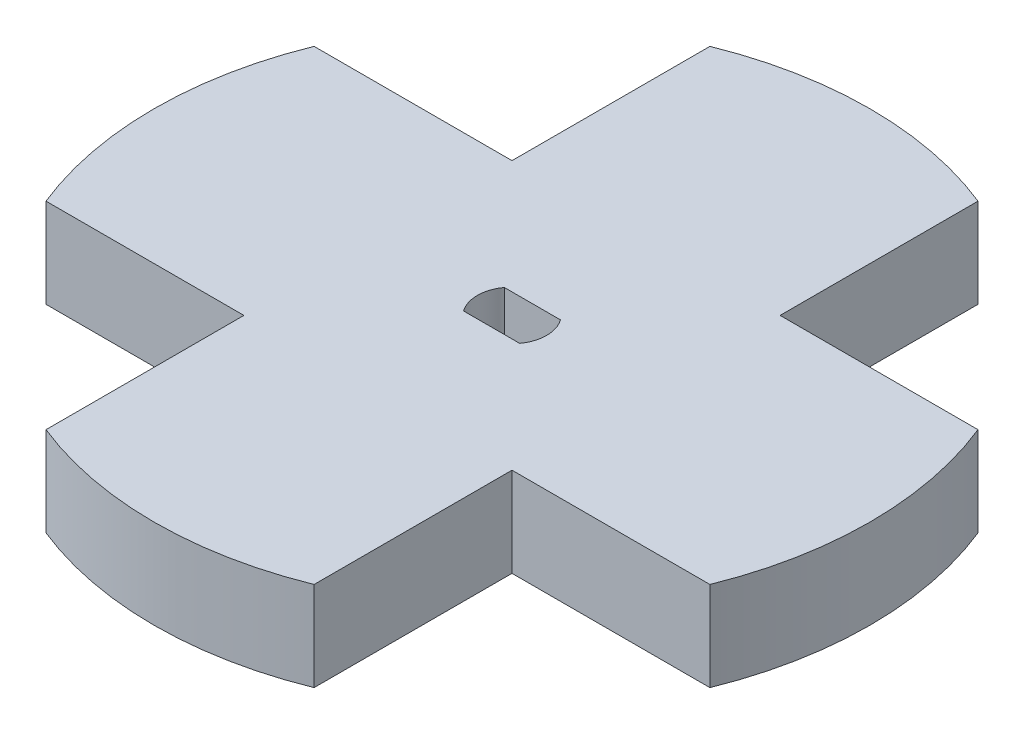
SolidWorks part; units mm, degrees
ref_plane "Front Plane" through (0, 0, 0) normal (0, 0, 1) x (1, 0, 0)
ref_plane "Top Plane" through (0, 0, 0) normal (0, 1, 0) x (1, 0, 0)
ref_plane "Right Plane" through (0, 0, 0) normal (1, 0, 0) x (0, 0, -1)
sketch "Sketch1" plane through (0, 0, 0) normal (0, 1, 0) x (1, 0, 0)
  line L0 (2.129, 43.8841) -> (2.129, 57.9466)
  line L1 (21.179, 43.8841) -> (21.179, 57.9466)
  line L2 (2.129, 24.8341) -> (2.129, 10.7716)
  line L3 (21.179, 24.8341) -> (21.179, 10.7716)
  line L4 (2.129, 43.8841) -> (-11.9336, 43.8841)
  line L5 (21.179, 43.8841) -> (35.2415, 43.8841)
  line L6 (2.129, 24.8341) -> (-11.9336, 24.8341)
  line L7 (21.179, 24.8341) -> (35.2415, 24.8341)
  line L8 (11.654, 35.8069) -> (13.6475, 35.8069)
  line L9 (11.654, 35.8069) -> (9.6604, 35.8069)
  line L10 (11.654, 32.9113) -> (9.6604, 32.9113)
  line L11 (11.654, 32.9113) -> (13.6475, 32.9113)
  arc A0 (35.2415, 24.8341) -> (35.2415, 43.8841) centre (11.654, 34.3591) ccw
  arc A2 (9.6604, 35.8069) -> (9.6604, 32.9113) centre (11.654, 34.3591) ccw
  arc A4 (13.6475, 32.9113) -> (13.6475, 35.8069) centre (11.654, 34.3591) ccw
  arc A5 (21.179, 57.9466) -> (2.129, 57.9466) centre (11.654, 34.3591) ccw
  arc A6 (-11.9336, 43.8841) -> (-11.9336, 24.8341) centre (11.654, 34.3591) ccw
  arc A7 (2.129, 10.7716) -> (21.179, 10.7716) centre (11.654, 34.3591) ccw
extrude "Boss-Extrude1" add sketch "Sketch1" along normal blind 6.35
